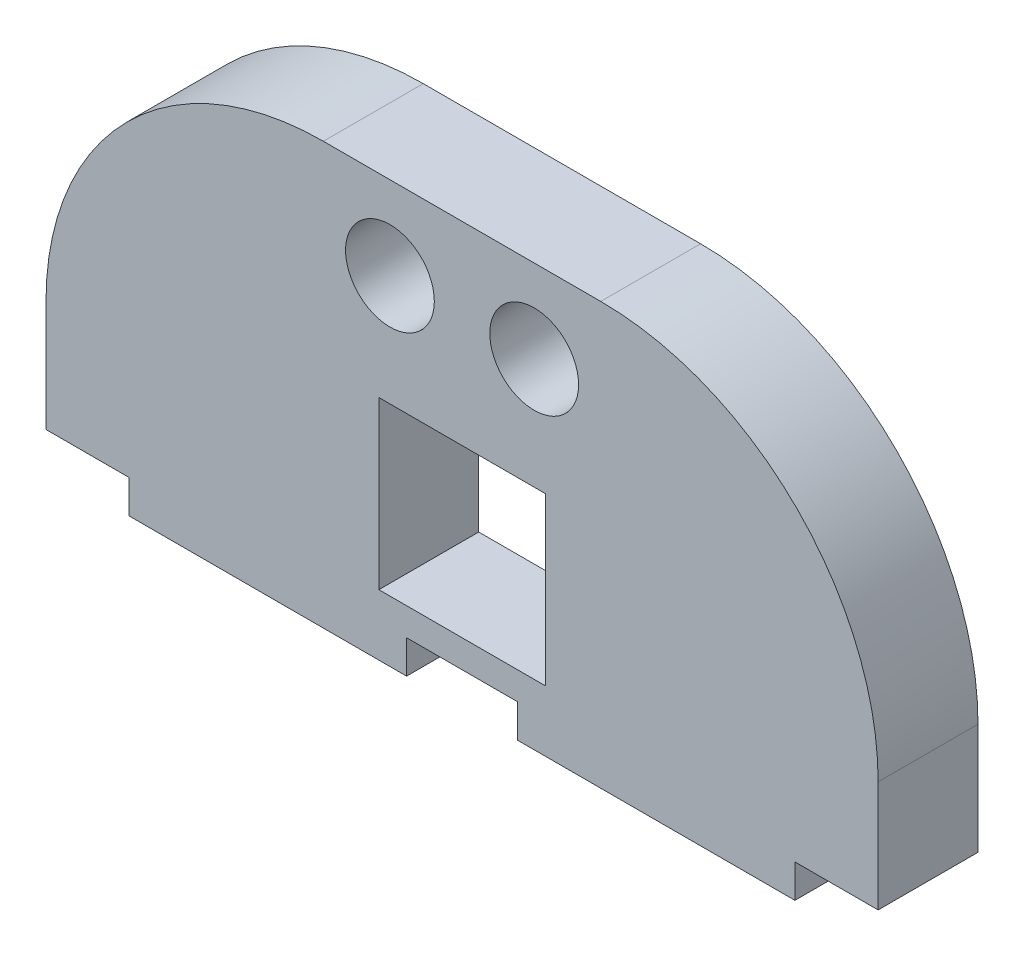
SolidWorks part; units mm, degrees
ref_plane "Plan de face" through (0, 0, 0) normal (0, 0, 1) x (1, 0, 0)
ref_plane "Plan de dessus" through (0, 0, 0) normal (0, 1, 0) x (1, 0, 0)
ref_plane "Plan de droite" through (0, 0, 0) normal (1, 0, 0) x (0, 0, -1)
sketch "Esquisse1" plane through (0, 0, 0) normal (0, 0, 1) x (1, 0, 0)
  line L0 (0, 0) -> (0, 20)
  line L2 (150, 0) -> (150, 20)
  line L3 (50, 70) -> (100, 70)
  line L4 (60, 35) -> (90, 35)
  line L5 (90, 35) -> (90, 5)
  line L6 (90, 5) -> (60, 5)
  line L7 (60, 5) -> (60, 35)
  line L8 (0, 0) -> (15, 0)
  line L9 (15, 0) -> (15, -6)
  line L10 (15, -6) -> (65, -6)
  line L11 (65, -6) -> (65, 0)
  line L12 (65, 0) -> (85, 0)
  line L13 (85, 0) -> (85, -6)
  line L14 (85, -6) -> (135, -6)
  line L15 (135, -6) -> (135, 0)
  line L16 (135, 0) -> (150, 0)
  arc A0 (0, 20) -> (50, 70) centre (50, 20) cw
  arc A1 (150, 20) -> (100, 70) centre (100, 20) ccw
  circle A2 centre (62, 55) radius 8
  circle A3 centre (88, 55) radius 8
  dimension "D10" = 26
  dimension "D14" = 16
  dimension "D15" = 16
  dimension "D1" = 150
  dimension "D2" = 50
  dimension "D3" = 50
  dimension "D4" = 50
  dimension "D5" = 20
  dimension "D6" = 60
  dimension "D7" = 15
  dimension "D8" = 30
  dimension "D9" = 30
  dimension "D11" = 15
  dimension "D12" = 15
  dimension "D13" = 62
  dimension "D16" = 50
  dimension "D17" = 20
  dimension "D18" = 50
  dimension "D19" = 15
  dimension "D20" = 6
  dimension "D21" = 6
  dimension "D22" = 5
extrude "Boss.-Extru.1" add sketch "Esquisse1" along normal blind 18
